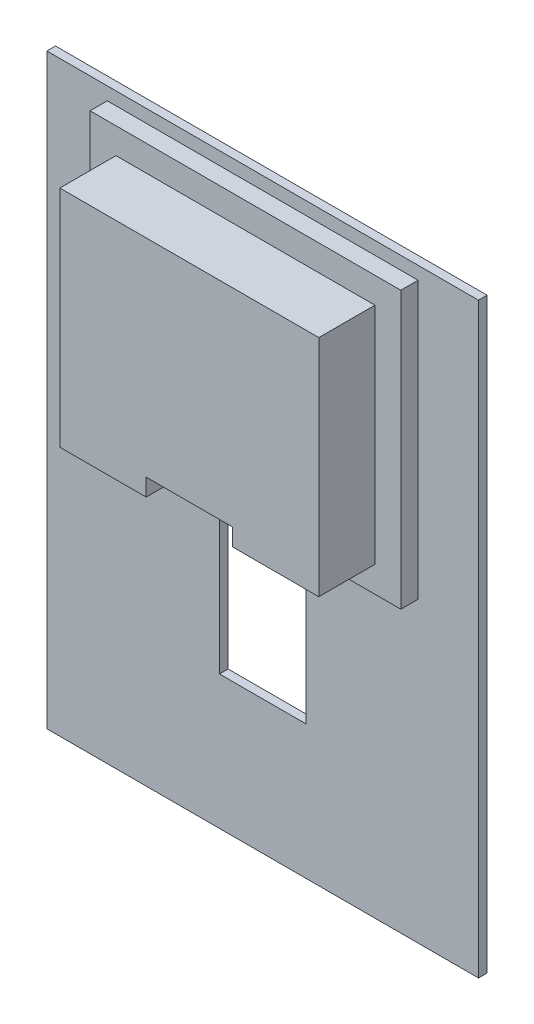
SolidWorks part; units mm, degrees
ref_plane "Plan de face" through (0, 0, 0) normal (0, 0, 1) x (1, 0, 0)
ref_plane "Plan de dessus" through (0, 0, 0) normal (0, 1, 0) x (1, 0, 0)
ref_plane "Plan de droite" through (0, 0, 0) normal (1, 0, 0) x (0, 0, -1)
sketch "Esquisse1" plane through (0, 0, 0) normal (0, 0, 1) x (1, 0, 0)
  line L0 (0, 0) -> (0, 87) construction
  line L1 (-50, -68) -> (50, -68)
  line L2 (-50, -68) -> (-50, 68)
  line L3 (-50, 68) -> (50, 68)
  line L4 (50, -68) -> (50, 68)
  line L5 (-50, -68) -> (50, 68) construction
  line L6 (-50, 68) -> (50, -68) construction
  line L7 (-34, 3) -> (34, 3)
  line L8 (-34, 3) -> (-34, 63)
  line L9 (-34, 63) -> (34, 63)
  line L10 (34, 3) -> (34, 63)
  line L11 (0, 87) -> (0, -87) construction
  line L13 (-10, 3) -> (10, 3)
  line L14 (-10, 3) -> (-10, -37)
  line L15 (-10, -68) -> (10, -68)
  line L16 (10, 3) -> (10, -37)
  line L17 (-10, 3) -> (10, 3)
  line L18 (-10, 3) -> (-10, -37)
  line L19 (-10, -37) -> (10, -37)
  line L20 (10, 3) -> (10, -37)
  point P0 (0, 0)
  dimension "D1" = 136
  dimension "D2" = 100
  dimension "D3" = 68
  dimension "D4" = 60
  dimension "D5" = 16
  dimension "D6" = 5
  dimension "D7" = 174
  dimension "D8" = 87
  dimension "D9" = 20
  dimension "D10" = 24
  dimension "D11" = 40
extrude "Boss.-Extru.1" add sketch "Esquisse1" along normal blind 2 contours L1 L4 L3 L2 L19 L14 L7 L8 L9 L10 L16
sketch "Esquisse2" plane through (0, 0, 2) normal (0, 0, 1) x (1, 0, 0)
  line L0 (-34, 63) -> (34, 63) construction
  line L1 (-36, 65) -> (36, 65)
  line L2 (-36, 65) -> (-36, 1)
  line L3 (-36, 1) -> (36, 1)
  line L4 (36, 65) -> (36, 1)
  line L5 (-34, 3) -> (-34, 63) construction
  line L6 (34, 3) -> (34, 63) construction
  line L7 (10, 3) -> (34, 3) construction
  line L9 (-34, 63) -> (34, 63)
  line L10 (-34, 63) -> (-34, 3)
  line L11 (-34, 3) -> (34, 3)
  line L12 (34, 63) -> (34, 3)
  line L13 (-10, 3) -> (10, 3)
  line L14 (-10, 3) -> (-10, 1)
  line L15 (-10, 1) -> (10, 1)
  line L16 (10, 3) -> (10, 1)
  line M6 (-10, -37) -> (-10, 3)
  line M7 (-10, 3) -> (-34, 3)
  line M8 (-34, 3) -> (-34, 63)
  line M9 (-34, 63) -> (34, 63)
  line M10 (34, 63) -> (34, 3)
  line M11 (34, 3) -> (10, 3)
  line M12 (10, 3) -> (10, -37)
  dimension "D1" = 2
  dimension "D2" = 2
  dimension "D3" = 2
  dimension "D4" = 2
  dimension "D5" = 20
extrude "Boss.-Extru.2" add sketch "Esquisse2" along normal blind 4 contours L4 L1 L2 L3 M6 M7 M8 M9 M10 M11 M12
sketch "Esquisse3" plane through (0, 0, 6) normal (0, 0, 1) x (1, 0, 0)
  line L1 (-34, 63) -> (34, 63)
  line L2 (-34, 63) -> (-34, 3)
  line L3 (-34, 3) -> (34, 3)
  line L4 (34, 63) -> (34, 3)
  line L5 (-28, 57) -> (28, 57)
  line L6 (-28, 57) -> (-28, 9)
  line L7 (-28, 9) -> (28, 9)
  line L8 (28, 57) -> (28, 9)
  dimension "D1" = 6
  dimension "D2" = 6
  dimension "D3" = 6
  dimension "D4" = 6
extrude "Boss.-Extru.3" add sketch "Esquisse3" against normal blind 2
sketch "Esquisse4" plane through (0, 0, 6) normal (0, 0, 1) x (1, 0, 0)
  line L1 (-28, 57) -> (28, 57)
  line L2 (-28, 57) -> (-28, 9)
  line L3 (-28, 9) -> (28, 9)
  line L4 (28, 57) -> (28, 9)
  line L5 (-30, 59) -> (30, 59)
  line L6 (-30, 59) -> (-30, 7)
  line L7 (-30, 7) -> (30, 7)
  line L8 (30, 59) -> (30, 7)
  dimension "D1" = 2
  dimension "D2" = 2
  dimension "D3" = 2
  dimension "D4" = 2
extrude "Boss.-Extru.4" add sketch "Esquisse4" along normal blind 13
sketch "Esquisse5" plane through (0, 0, 19) normal (0, 0, 1) x (1, 0, 0)
  line L1 (-28, 57) -> (28, 57)
  line L2 (-28, 57) -> (-28, 9)
  line L3 (-28, 9) -> (28, 9)
  line L4 (28, 57) -> (28, 9)
extrude "Boss.-Extru.5" add sketch "Esquisse5" against normal blind 2
sketch "Esquisse6" plane through (0, 0, 19) normal (0, 0, 1) x (1, 0, 0)
  line L1 (-10, 1) -> (10, 1)
  line L2 (-10, 1) -> (-10, 11)
  line L3 (-10, 11) -> (10, 11)
  line L4 (10, 1) -> (10, 11)
  dimension "D1" = 20
  dimension "D2" = 10
extrude "Enlèv. mat.-Extru.1" cut sketch "Esquisse6" against normal blind 35
